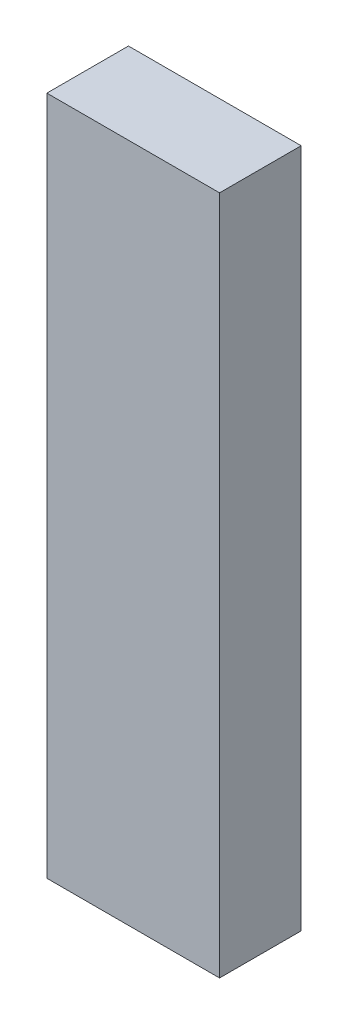
SolidWorks part; units mm, degrees
ref_plane "Front Plane" through (0, 0, 0) normal (0, 0, 1) x (1, 0, 0)
ref_plane "Top Plane" through (0, 0, 0) normal (0, 1, 0) x (1, 0, 0)
ref_plane "Right Plane" through (0, 0, 0) normal (1, 0, 0) x (0, 0, -1)
sketch "Sketch1" plane through (0, 0, 0) normal (0, 0, 1) x (1, 0, 0)
  line L1 (-3.175, -12.5) -> (3.175, -12.5)
  line L2 (-3.175, -12.5) -> (-3.175, 12.5)
  line L3 (-3.175, 12.5) -> (3.175, 12.5)
  line L4 (3.175, -12.5) -> (3.175, 12.5)
  line L5 (-3.175, -12.5) -> (3.175, 12.5) construction
  line L6 (-3.175, 12.5) -> (3.175, -12.5) construction
  point P0 (0, 0)
  dimension "D1" = 25
  dimension "D2" = 6.35
extrude "Boss-Extrude1" add sketch "Sketch1" along normal blind 3
